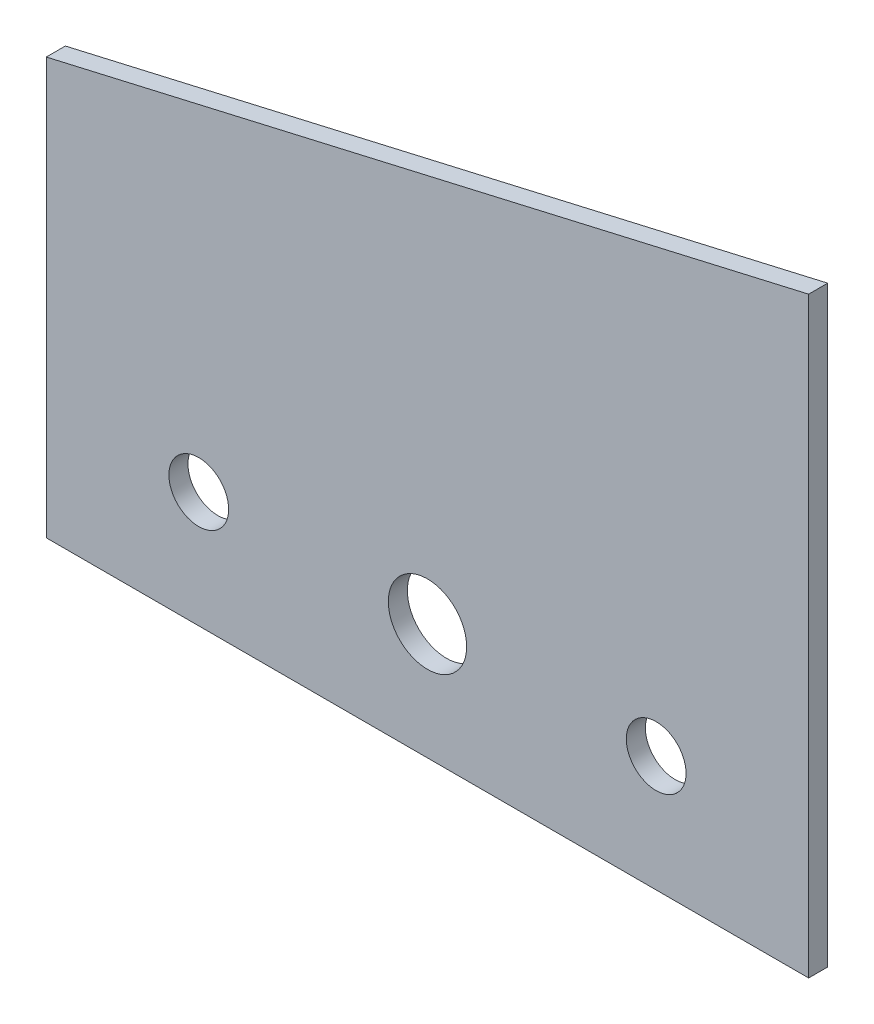
SolidWorks part; units mm, degrees
material "AISI 1010 Steel, hot rolled bar"
ref_plane "Front Plane" through (0, 0, 0) normal (0, 0, 1) x (1, 0, 0)
ref_plane "Top Plane" through (0, 0, 0) normal (0, 1, 0) x (1, 0, 0)
ref_plane "Right Plane" through (0, 0, 0) normal (1, 0, 0) x (0, 0, -1)
sketch "Sketch1" plane through (0, 0, 0) normal (0, 0, 1) x (1, 0, 0)
  line L2 (1385.5223, -68.9842) -> (1385.5223, -118.3135)
  line L3 (1385.5223, -118.3135) -> (1322.0223, -118.3135)
  line L4 (1322.0223, -118.3135) -> (1322.0223, -83.6274)
  line L6 (1322.0223, -83.6274) -> (1385.5223, -68.9842)
  circle A0 centre (1334.7223, -108.6615) radius 2.4892
  circle A1 centre (1372.8223, -108.6615) radius 2.4892
  circle A2 centre (1353.7723, -108.6615) radius 3.2639
  point P10 (1353.7723, -118.3135)
  dimension "D8" = 6.5278
  dimension "D10" = 4.9784
  dimension "D1" = 63.5
  dimension "D2" = 77.014
  dimension "D3" = 49.3293
  dimension "D4" = 12.7
  dimension "D5" = 12.7
  dimension "D9" = 9.652
extrude "Boss-Extrude1" add sketch "Sketch1" along normal blind 1.5875 contours L3 L4 L6 L2
sketch "Sketch2" plane through (0, 0, 1.5875) normal (0, 0, 1) x (1, 0, 0)
  circle A0 centre (1353.7723, -108.6615) radius 3.2639 construction
  circle A1 centre (1353.7723, -108.6615) radius 3.2639
